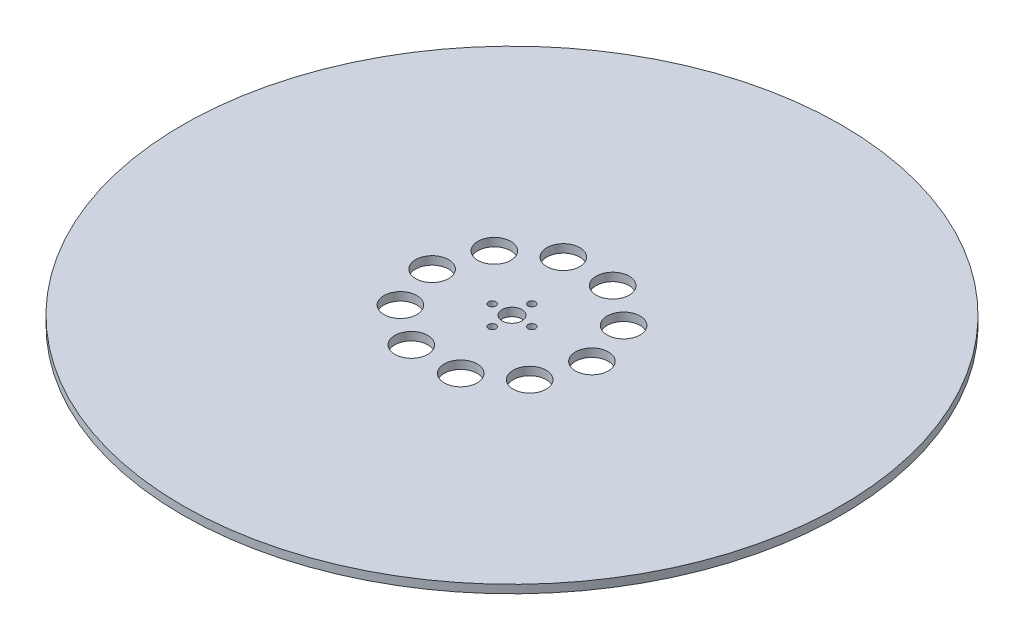
SolidWorks part; units mm, degrees
material "AISI 1020 Acier laminé à froid"
ref_plane "Plan de face" through (0, 0, 0) normal (0, 0, 1) x (1, 0, 0)
ref_plane "Plan de dessus" through (0, 0, 0) normal (0, 1, 0) x (1, 0, 0)
ref_plane "Plan de droite" through (0, 0, 0) normal (1, 0, 0) x (0, 0, -1)
sketch "Esquisse1" plane through (0, 0, 0) normal (0, 1, 0) x (1, 0, 0)
  circle A1 centre (0, 0) radius 200
  circle A2 centre (-14.9856, 46.121) radius 10
  circle A3 centre (14.9856, 46.121) radius 10
  circle A4 centre (39.2329, 28.5044) radius 10
  circle A5 centre (48.4945, 0) radius 10
  circle A6 centre (39.2329, -28.5044) radius 10
  circle A7 centre (14.9856, -46.121) radius 10
  circle A8 centre (-14.9856, -46.121) radius 10
  circle A9 centre (-39.2329, -28.5044) radius 10
  circle A10 centre (-48.4945, 0) radius 10
  circle A11 centre (-39.2329, 28.5044) radius 10
  circle A13 centre (0, 12) radius 2.25
  circle A14 centre (0, 0) radius 6
  circle A18 centre (12, 0) radius 2.25
  circle A19 centre (0, -12) radius 2.25
  circle A20 centre (-12, 0) radius 2.25
  point P27 (0, 0)
  point P37 (1.7436, 2.5966)
  point P38 (0, 0)
  dimension "D1" = 20
  dimension "D2" = 400
  dimension "D4" = 4.5
  dimension "D5" = 4
  dimension "D6" = 12
  dimension "D7" = 12
  dimension "D3" = 10
extrude "Boss.-Extru.1" add sketch "Esquisse1" along normal blind 5
